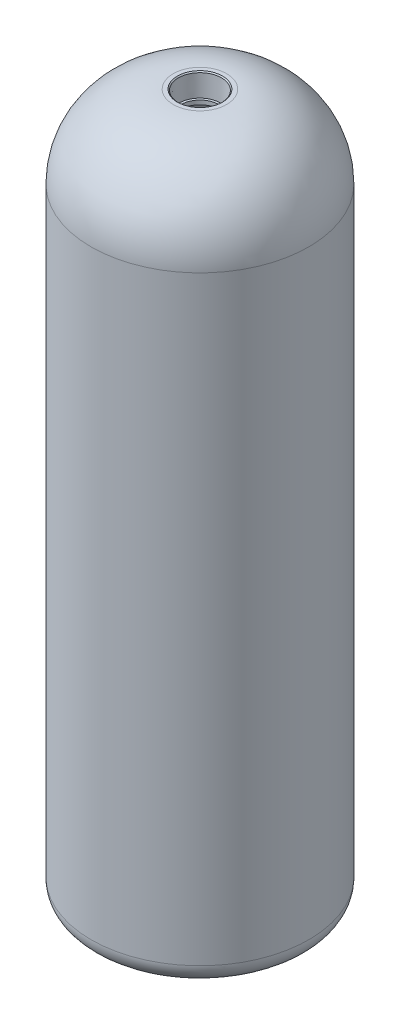
SolidWorks part; units mm, degrees
ref_plane "Front Plane" through (0, 0, 0) normal (0, 0, 1) x (1, 0, 0)
ref_plane "Top Plane" through (0, 0, 0) normal (0, 1, 0) x (1, 0, 0)
ref_plane "Right Plane" through (0, 0, 0) normal (1, 0, 0) x (0, 0, -1)
sketch "Sketch4" plane through (0, 0, 0) normal (1, 0, 0) x (0, 0, -1)
  line L0 (0, 0) -> (-54.61, 0)
  line L1 (-67.31, 12.7) -> (-67.31, 383.54)
  line L2 (-50.8, 379.73) -> (-50.8, 29.21)
  line L3 (-38.1, 16.51) -> (0, 16.51)
  line L4 (0, 434.34) -> (0, 0) construction
  line L5 (-16.51, 434.34) -> (0, 434.34)
  line L6 (-12.7, 417.83) -> (0, 417.83)
  arc A0 (-38.1, 16.51) -> (-50.8, 29.21) centre (-38.1, 29.21) cw
  arc A1 (-54.61, 0) -> (-67.31, 12.7) centre (-54.61, 12.7) cw
  arc A2 (-50.8, 379.73) -> (-12.7, 417.83) centre (-12.7, 379.73) cw
  arc A3 (-67.31, 383.54) -> (-16.51, 434.34) centre (-16.51, 383.54) cw
  point P2 (0.5884, 434.34)
  point P14 (-67.31, 0)
  point P19 (-50.8, 417.83)
  dimension "D5" = 12.7
  dimension "D7" = 38.1
  dimension "D2" = 50.8
  dimension "D1" = 67.31
  dimension "D3" = 16.51
  dimension "D4" = 16.51
  dimension "D6" = 434.34
  dimension "D8" = 16.51
revolve "Revolve1" add sketch "Sketch4" angle 360 about L4
sketch "Sketch5" plane through (0, 434.34, 0) normal (0, 1, 0) x (1, 0, 0)
  point P0 (0, 0)
hole_wizard "3/4 NPT Tapped Hole2" positions "Sketch5" profile "Sketch6" size "3/4" standard "ANSI Inch"
sketch "Sketch6" plane through (0, 434.34, 0) normal (1, 0, 0) x (0, 0, 1)
  line L0 (0, 0) -> (0, 30.0276)
  line L1 (11.5062, 23.114) -> (0, 30.0276)
  line L2 (-11.5062, 23.114) -> (0, 30.0276) construction
  line L3 (11.5062, 23.114) -> (11.5062, 13.97)
  line L4 (11.5062, 13.97) -> (12.9332, 13.97)
  line L5 (12.9332, 13.97) -> (13.3325, 0.635)
  line L6 (13.3325, 0.635) -> (13.9675, 0)
  line L7 (13.9675, 0) -> (0, 0)
  line L8 (0, -6.35) -> (0, 107.95) construction
  line L9 (-13.3325, 0.635) -> (-13.9675, 0) construction
  line L11 (-11.5062, 13.97) -> (-12.9332, 13.97) construction
  line L12 (-12.9332, 13.97) -> (-13.3325, 0.635) construction
  dimension "Tap Drill Dia." = 23.0124
  dimension "Tap Drill Depth" = 23.114
  dimension "Thread Dia." = 26.665
  dimension "Thread Angle" = 3.43
  dimension "Thread Depth" = 13.97
  dimension "C'Sink Dia." = 27.935
  dimension "C'Sink Angle" = 90
  dimension "Drill Angle" = 118
equation "\"D4@Sketch4\"=\"D3@Sketch4\""
equation "\"D8@Sketch4\"=\"D3@Sketch4\""
